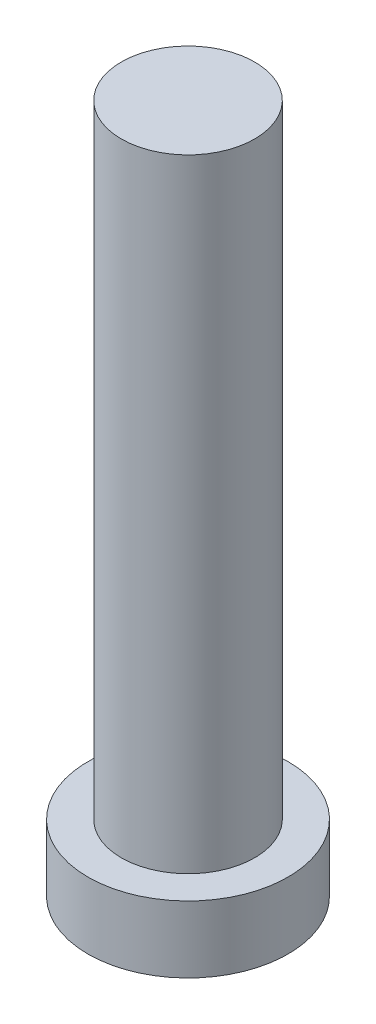
SolidWorks part; units mm, degrees
ref_plane "Alzado" through (0, 0, 0) normal (0, 0, 1) x (1, 0, 0)
ref_plane "Planta" through (0, 0, 0) normal (0, 1, 0) x (1, 0, 0)
ref_plane "Vista lateral" through (0, 0, 0) normal (1, 0, 0) x (0, 0, -1)
sketch "Croquis1" plane through (0, 0, 0) normal (0, 1, 0) x (1, 0, 0)
  circle A0 centre (0, 0) radius 7.5
extrude "Saliente-Extruir1" add sketch "Croquis1" along normal blind 5
sketch "Croquis2" plane through (0, 5, 0) normal (0, 1, 0) x (1, 0, 0)
  circle A0 centre (0, 0) radius 5
extrude "Saliente-Extruir2" add sketch "Croquis2" along normal blind 20 contours A0
scale "Escala1" bodies to scale 102 scale about centroid uniform scaling yes scale factor 0.75
sketch "Croquis4" plane through (0, 21.375, 0) normal (0, 1, 0) x (1, 0, 0)
  circle A0 centre (0, 0) radius 3.75
extrude "Saliente-Extruir3" add sketch "Croquis4" along normal blind 20
